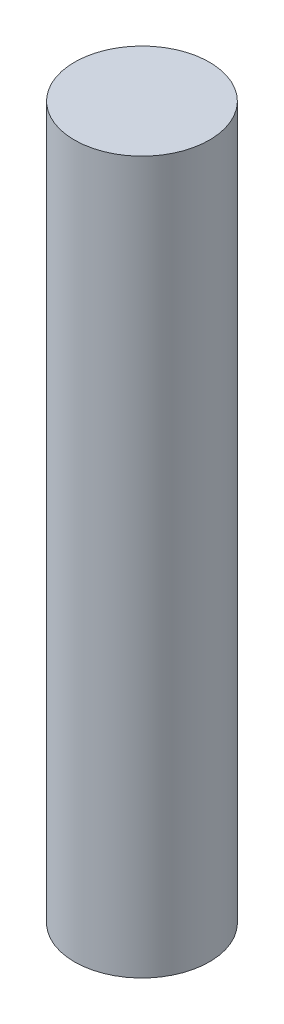
SolidWorks part; units mm, degrees
ref_plane "Front Plane" through (0, 0, 0) normal (0, 0, 1) x (1, 0, 0)
ref_plane "Top Plane" through (0, 0, 0) normal (0, 1, 0) x (1, 0, 0)
ref_plane "Right Plane" through (0, 0, 0) normal (1, 0, 0) x (0, 0, -1)
sketch "Sketch1" plane through (0, 0, 0) normal (0, 1, 0) x (1, 0, 0)
  circle A0 centre (0, 0) radius 275
  dimension "D1" = 550
extrude "Boss-Extrude1" add sketch "Sketch1" along normal blind 2900
